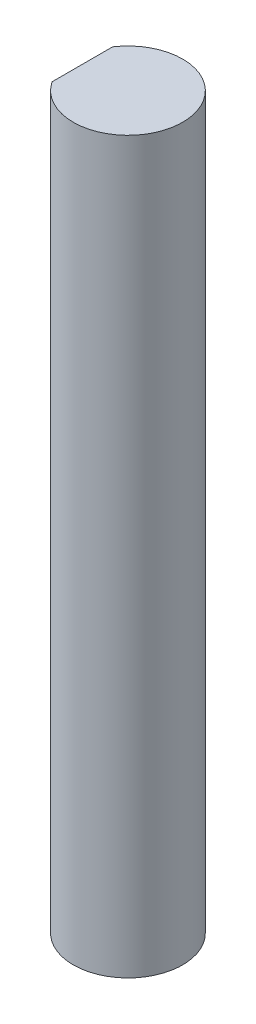
SolidWorks part; units mm, degrees
material "Alloy Steel"
ref_plane "Front Plane" through (0, 0, 0) normal (0, 0, 1) x (1, 0, 0)
ref_plane "Top Plane" through (0, 0, 0) normal (0, 1, 0) x (1, 0, 0)
ref_plane "Right Plane" through (0, 0, 0) normal (1, 0, 0) x (0, 0, -1)
sketch "Sketch1" plane through (0, 0, 0) normal (0, 1, 0) x (1, 0, 0)
  line L0 (-2.5, 1.6583) -> (-2.5, -1.6583)
  arc A0 (-2.5, -1.6583) -> (-2.5, 1.6583) centre (0, 0) ccw
  point P1 (3, 0)
  dimension "D1" = 6
  dimension "D2" = 5.5
extrude "Boss-Extrude1" add sketch "Sketch1" along normal blind 40
